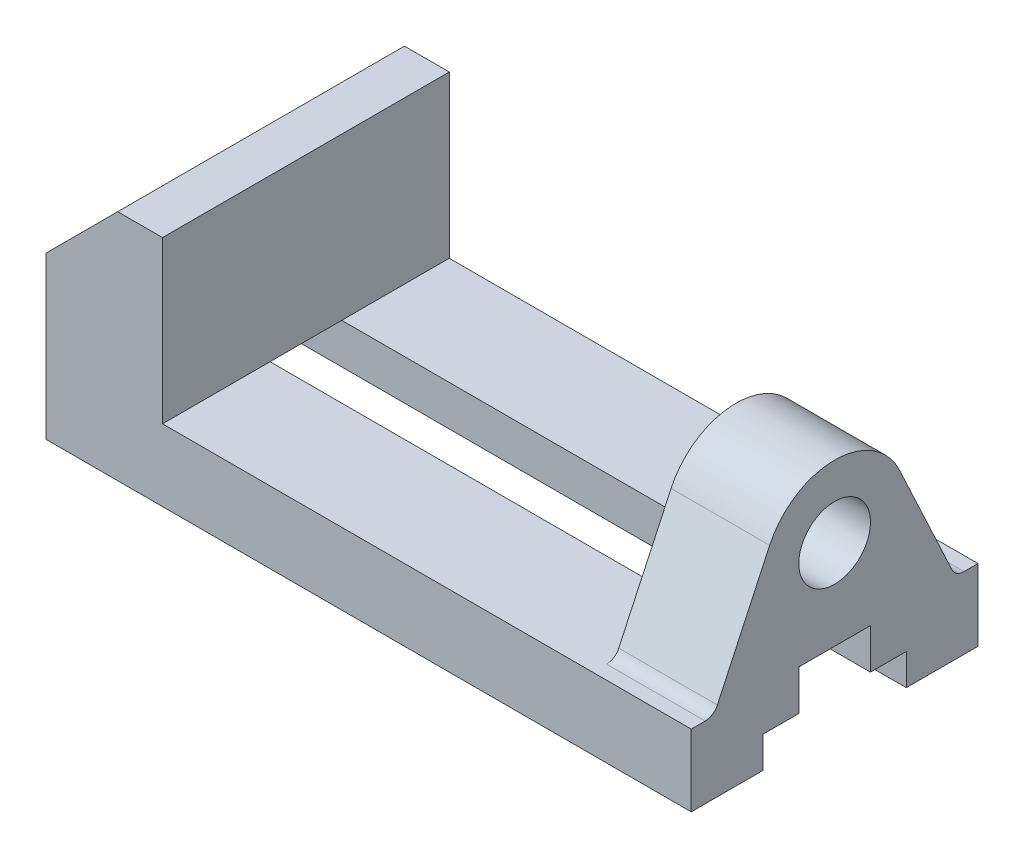
SolidWorks part; units mm, degrees
ref_plane "Front Plane" through (0, 0, 0) normal (0, 0, 1) x (1, 0, 0)
ref_plane "Top Plane" through (0, 0, 0) normal (0, 1, 0) x (1, 0, 0)
ref_plane "Right Plane" through (0, 0, 0) normal (1, 0, 0) x (0, 0, -1)
sketch "Sketch1" plane through (0, 0, 0) normal (0, 0, 1) x (1, 0, 0)
  line L0 (0, 0) -> (144, 0)
  line L1 (144, 0) -> (144, 52)
  line L2 (144, 52) -> (122, 52)
  line L3 (122, 52) -> (122, 16)
  line L4 (122, 16) -> (26, 16)
  line L5 (26, 16) -> (26, 52)
  line L6 (26, 52) -> (16, 52)
  line L7 (0, 0) -> (0, 36)
  line L8 (0, 36) -> (16, 52)
extrude "Extrude1" add sketch "Sketch1" against normal blind 64
sketch "Sketch2" plane through (144, 0, 0) normal (1, 0, 0) x (0, 0, -1)
  line L0 (48, 0) -> (64, 0)
  line L3 (0, 0) -> (16, 0)
  line L4 (64, 0) -> (0, 0) construction
  line L5 (16, 0) -> (16, 7)
  line L6 (16, 7) -> (24, 7)
  line L7 (24, 7) -> (24, 16)
  line L8 (24, 16) -> (40, 16)
  line L9 (40, 16) -> (40, 7)
  line L10 (40, 7) -> (48, 7)
  line L11 (48, 7) -> (48, 0)
  line L12 (-70.8211, -59.5297) -> (-70.6213, -59.6304)
  dimension "D1" = 8
  dimension "D4" = 9
  dimension "D2" = 7
  dimension "D3" = 7
extrude "Extrude2" cut sketch "Sketch2" against normal through all
sketch "Sketch3" plane through (144, 0, 0) normal (1, 0, 0) x (0, 0, -1)
  line L0 (64, 16) -> (64, 36) construction
  line L1 (64, 36) -> (0, 36) construction
  line L2 (64, 0) -> (64, 52) construction
  line L3 (32, 36) -> (32, 73.8592) construction
  line L4 (17.4991, 42.7619) -> (5.8275, 17.7321)
  line L5 (46.5009, 42.7619) -> (58.1725, 17.7321)
  line L6 (117.8569, 16) -> (-34.5358, 16) construction
  line L7 (0, 16) -> (3.1086, 16)
  line L8 (0, 0) -> (0, 52) construction
  line L9 (60.8914, 16) -> (64, 16)
  line L11 (0, 16) -> (0, 52)
  line L12 (0, 52) -> (64, 52)
  line L13 (64, 52) -> (64, 16)
  circle A0 centre (32, 36) radius 8
  arc A1 (46.5009, 42.7619) -> (17.4991, 42.7619) centre (32, 36) ccw
  arc A2 (3.1086, 16) -> (5.8275, 17.7321) centre (3.1086, 19) ccw
  arc A3 (60.8914, 16) -> (58.1725, 17.7321) centre (60.8914, 19) cw
  point P25 (5.0198, 16)
  point P28 (58.9802, 16)
  line M4 (64, 0) -> (64, 52)
  line M5 (64, 52) -> (0, 52)
  line M6 (0, 52) -> (0, 0)
  dimension "D1" = 50
  dimension "D3" = 32
  dimension "D4" = 3
  dimension "D2" = 25
extrude "Extrude9" cut sketch "Sketch3" against normal blind 22 contours L7 A2 L4 A1 L12 M6 | A3 L9 A1 L5 M4 M5 | A0
sketch "Sketch4" plane through (0, 0, 0) normal (0, -1, 0) x (1, 0, 0)
  line L0 (144, -10) -> (0, -10) construction
  line L1 (144, -16) -> (144, 0) construction
  line L2 (0, -16) -> (0, 0) construction
  line L3 (0, 0) -> (144, 0) construction
  line L4 (0, -54) -> (144, -54) construction
  line L5 (0, -64) -> (0, -48) construction
  line L6 (144, -64) -> (144, -48) construction
  circle A0 centre (38, -10) radius 3
  circle A1 centre (108, -10) radius 3
  circle A2 centre (38, -54) radius 3
  circle A3 centre (108, -54) radius 3
  dimension "D1" = 36
  dimension "D4" = 44
  dimension "D2" = 70
  dimension "D3" = 10
  dimension "D5" = 70
  dimension "D6" = 36
hole_wizard "Ø6.0 (6) Diameter Hole1" positions "3DSketch1" profile "Sketch5" hole size "Ø6.0" standard "Ansi Metric"
sketch3d "3DSketch1"
  point P0 (38, 0, -10)
  point P3 (108, 0, -10)
  point P6 (108, 0, -54)
  point P9 (38, 0, -54)
sketch "Sketch5" plane through (38, 0, -10) normal (1, 0, 0) x (0, 0, -1)
  line L0 (0, 0) -> (0, 11.8026)
  line L1 (0, 11.8026) -> (3, 10)
  line L2 (3, 10) -> (3, 0)
  line L5 (3, 0) -> (0, 0)
  line L10 (0, 11.8026) -> (-3, 10) construction
  line L11 (0, -6.35) -> (0, 107.95) construction
  dimension "Hole Dia." = 6
  dimension "Hole Depth" = 10
  dimension "Drill Angle" = 118
